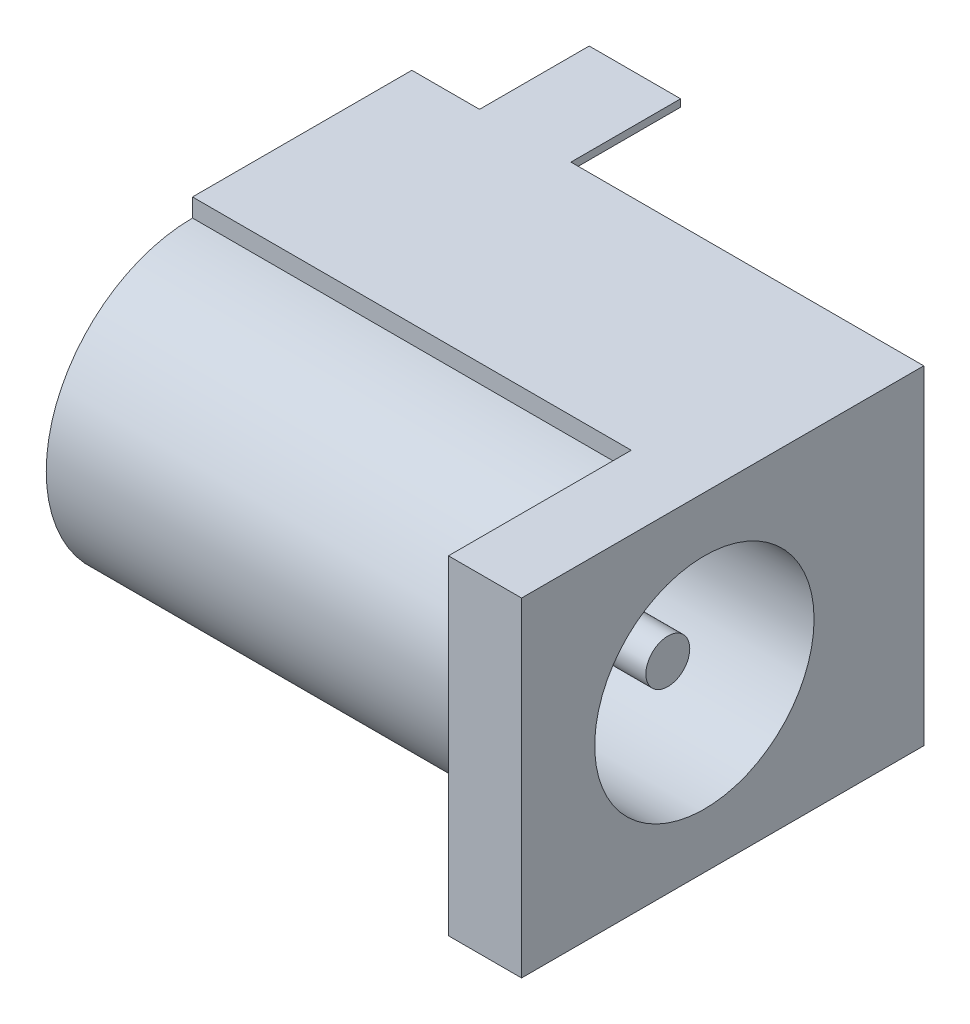
SolidWorks part; units mm, degrees
ref_plane "前视基准面" through (0, 0, 0) normal (0, 0, 1) x (1, 0, 0)
ref_plane "上视基准面" through (0, 0, 0) normal (0, 1, 0) x (1, 0, 0)
ref_plane "右视基准面" through (0, 0, 0) normal (1, 0, 0) x (0, 0, -1)
sketch "草图1" plane through (0, 0, 0) normal (0, 0, 1) x (1, 0, 0)
  line L0 (-1000, 0) -> (49000, 0) construction
  line L1 (0, -1000) -> (0, 49000) construction
  line L2 (-7, 4.5) -> (7, 4.5)
  line L3 (7, 4.5) -> (7, -4.5)
  line L4 (-7, 4.5) -> (-7, -4.5)
  line L5 (-7, -4.5) -> (7, -4.5)
  point P10 (0, 4.5)
  point P11 (7, 0)
  point P12 (-7, 0)
  dimension "D1" = 9
  dimension "D2" = 14
extrude "凸台-拉伸1" add sketch "草图1" along normal blind 11
sketch "草图3" plane through (7, 0, 0) normal (1, 0, 0) x (0, 0, -1)
  line L0 (-11, -4.5) -> (0, -4.5) construction
  line L1 (-11, -4.5) -> (-11, 4.5) construction
  circle A0 centre (-6, 0) radius 3
  dimension "D1" = 4.5
  dimension "D2" = 5
  dimension "D3" = 6
extrude "切除-拉伸1" cut sketch "草图3" against normal blind 8
sketch "草图5" plane through (-1, 0, 0) normal (1, 0, 0) x (0, 0, -1)
  circle A0 centre (-6, 0) radius 0.6
extrude "凸台-拉伸2" add sketch "草图5" along normal blind 7
sketch "草图6" plane through (-7, 0, 0) normal (-1, 0, 0) x (0, 0, 1)
  line L0 (11, -4.5) -> (0, -4.5) construction
  line L1 (11, 4.5) -> (11, -4.5) construction
  line L2 (6, 4) -> (6, 4.5)
  line L3 (11, 4.5) -> (0, 4.5) construction
  line L4 (6, 4.5) -> (11, 4.5)
  line L5 (11, 4.5) -> (11, -4.5)
  line L6 (11, -4.5) -> (6, -4.5)
  line L7 (6, -4.5) -> (6, -4)
  arc A0 (6, -4) -> (6, 4) centre (6, 0) ccw
  point P2 (5.5, -4.5)
  dimension "D1" = 4.5
  dimension "D2" = 5
  dimension "D3" = 8
extrude "切除-拉伸2" cut sketch "草图6" against normal blind 12
sketch "草图7" plane through (0, 0, 0) normal (0, 0, -1) x (-1, 0, 0)
  line L0 (-1000, 0) -> (49000, 0) construction
  line L1 (0, -1000) -> (0, 49000) construction
  line L2 (6.8, 1.5) -> (7, 1.5)
  line L3 (7, 4.5) -> (7, -4.5) construction
  line L4 (7, 1.5) -> (7, -1.5)
  line L5 (6.8, 1.5) -> (6.8, -1.5)
  line L6 (6.8, -1.5) -> (7, -1.5)
  line L7 (6.9, 1.5) -> (6.9, -1.5) construction
  line L8 (-0.1, 1.1874) -> (-0.1, -1.6933) construction
  line L9 (-0.2, 1.25) -> (0, 1.25)
  line L10 (0, 1.25) -> (0, -1.25)
  line L11 (-0.2, 1.25) -> (-0.2, -1.25)
  line L12 (-0.2, -1.25) -> (0, -1.25)
  line L13 (3.9, 5.0712) -> (3.9, -5.2844) construction
  line L14 (2.65, 4.5) -> (5.15, 4.5)
  line L15 (-7, 4.5) -> (7, 4.5) construction
  line L16 (5.15, 4.5) -> (5.15, 4.3)
  line L17 (5.15, 4.3) -> (2.65, 4.3)
  line L18 (2.65, 4.5) -> (2.65, 4.3)
  point P10 (6.8, 0)
  point P13 (7, 0)
  point P21 (0, 0)
  point P22 (-0.1, 1.25)
  point P24 (-0.2, 0)
  point P32 (3.9, 4.5)
  point P34 (3.9, 4.3)
  dimension "D1" = 3
  dimension "D2" = 0.2
  dimension "D3" = 7
  dimension "D4" = 2.5
  dimension "D5" = 0.2
  dimension "D6" = 3
  dimension "D7" = 0.2
  dimension "D8" = 2.5
extrude "凸台-拉伸3" add sketch "草图7" along normal blind 3
